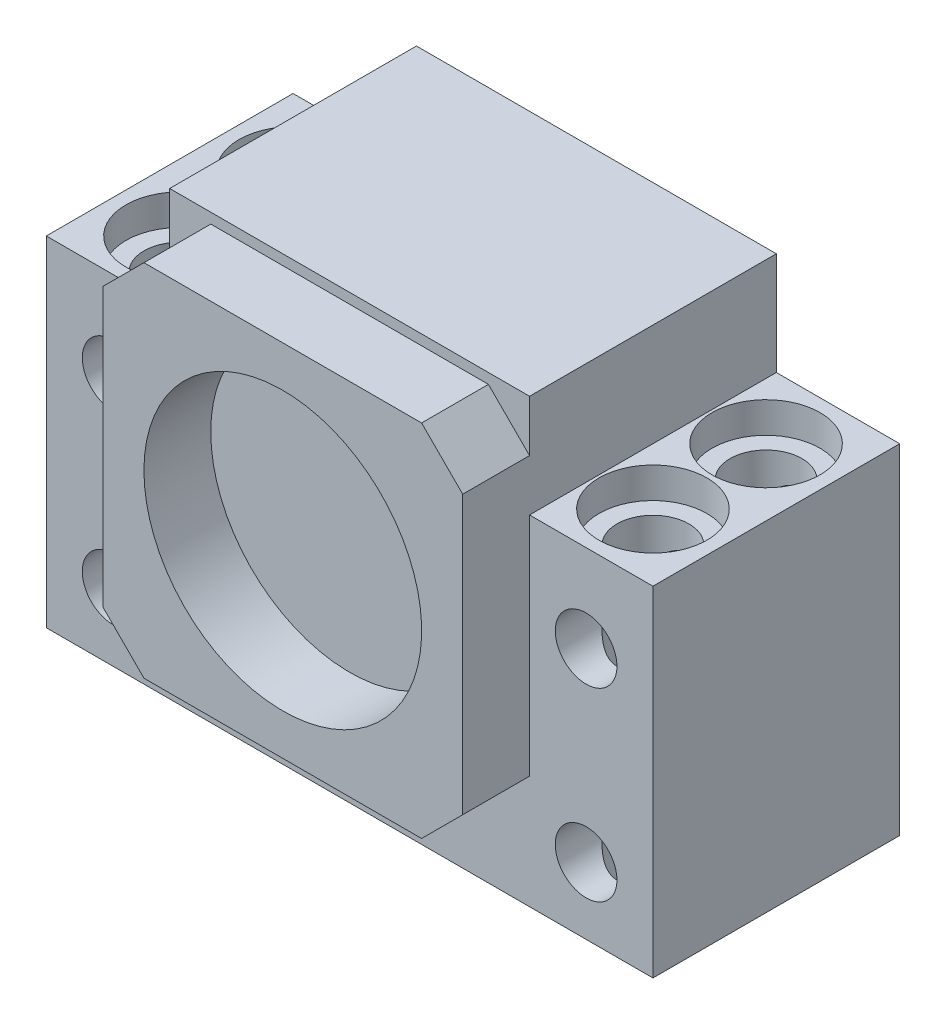
SolidWorks part; units mm, degrees
ref_plane "Plan de face" through (0, 0, 0) normal (0, 0, 1) x (1, 0, 0)
ref_plane "Plan de dessus" through (0, 0, 0) normal (0, 1, 0) x (1, 0, 0)
ref_plane "Plan de droite" through (0, 0, 0) normal (1, 0, 0) x (0, 0, -1)
sketch "Esquisse1" plane through (0, 0, 0) normal (0, 0, 1) x (1, 0, 0)
  line L0 (0, 25.1018) -> (0, -24.5) construction
  line L1 (-17.5, 18.5) -> (17.5, 18.5)
  line L2 (-29.5, 8.5) -> (-29.5, -24.5)
  line L3 (-29.5, -24.5) -> (29.5, -24.5)
  line L4 (29.5, 8.5) -> (29.5, -24.5)
  line L7 (-29.5, 8.5) -> (-17.5, 8.5)
  line L8 (-17.5, 18.5) -> (-17.5, 8.5)
  line L11 (29.5, 8.5) -> (17.5, 8.5)
  line L12 (17.5, 18.5) -> (17.5, 8.5)
  circle A0 centre (0, 0) radius 13.5
  circle A1 centre (-23, -18) radius 3
  circle A2 centre (-23, 0) radius 3
  circle A3 centre (23, 0) radius 3
  circle A4 centre (23, -18) radius 3
  dimension "D3" = 27
  dimension "D11" = 6
  dimension "D1" = 33
  dimension "D4" = 59
  dimension "D5" = 43
  dimension "D6" = 35
  dimension "D7" = 6.5
  dimension "D8" = 24.5
  dimension "D9" = 6.5
  dimension "D10" = 6.5
extrude "Boss.-Extru.1" add sketch "Esquisse1" along normal blind 24
sketch "Esquisse2" plane through (0, 8.5, 0) normal (0, 1, 0) x (1, 0, 0)
  line L0 (29.5, -24) -> (17.5, -24) construction
  line L1 (29.5, 0) -> (17.5, 0) construction
  line L2 (-29.5, -24) -> (-29.5, 0) construction
  line L3 (29.5, -24) -> (29.5, 0) construction
  circle A0 centre (-23, -17.5) radius 3.5
  circle A1 centre (23, -17.5) radius 3.5
  circle A2 centre (23, -6.5) radius 3.5
  circle A3 centre (-23, -6.5) radius 3.5
  point P22 (-23, -17.5)
  point P23 (23, -17.5)
  dimension "D1" = 7
  dimension "D2" = 6.5
  dimension "D3" = 6.5
  dimension "D4" = 6.5
  dimension "D5" = 6.5
extrude "Enlèv. mat.-Extru.1" cut sketch "Esquisse2" against normal up to surface (33 mm away) up to face at (0, -24.5, 12)
sketch "Esquisse3" plane through (0, 8.5, 0) normal (0, 1, 0) x (1, 0, 0)
  circle A0 centre (-23, -17.5) radius 5.25
  circle A1 centre (23, -17.5) radius 5.25
  circle A2 centre (-23, -6.5) radius 5.25
  circle A3 centre (23, -6.5) radius 5.25
  dimension "D1" = 10.5
extrude "Enlèv. mat.-Extru.2" cut sketch "Esquisse3" against normal blind 3
sketch "Esquisse5" plane through (0, 0, 24) normal (0, 0, 1) x (1, 0, 0)
  line L0 (-17.5, 13.5) -> (-17.5, -13.5)
  line L2 (-13.5, -17.5) -> (13.5, -17.5)
  line L3 (17.5, -13.5) -> (17.5, 13.5)
  line L5 (13.5, 17.5) -> (-13.5, 17.5)
  line L7 (-17.5, 18.5) -> (-17.5, 8.5) construction
  line L8 (17.5, 8.5) -> (17.5, 18.5) construction
  line L9 (-17.5, 17.5) -> (17.5, -17.5) construction
  line L10 (17.5, 17.5) -> (-17.5, -17.5) construction
  line L12 (-13.5, 17.5) -> (-17.5, 13.5)
  line L13 (13.5, 17.5) -> (17.5, 13.5)
  line L14 (17.5, -13.5) -> (13.5, -17.5)
  line L15 (-17.5, -13.5) -> (-13.5, -17.5)
  circle A0 centre (0, 0) radius 13.506
  point P0 (0, 0)
  dimension "D1" = 4
  dimension "D2" = 45
  dimension "D3" = 45
  dimension "D4" = 4
  dimension "D5" = 45
  dimension "D6" = 4
  dimension "D7" = 4
  dimension "D8" = 45
extrude "Boss.-Extru.2" add sketch "Esquisse5" along normal blind 6.5
